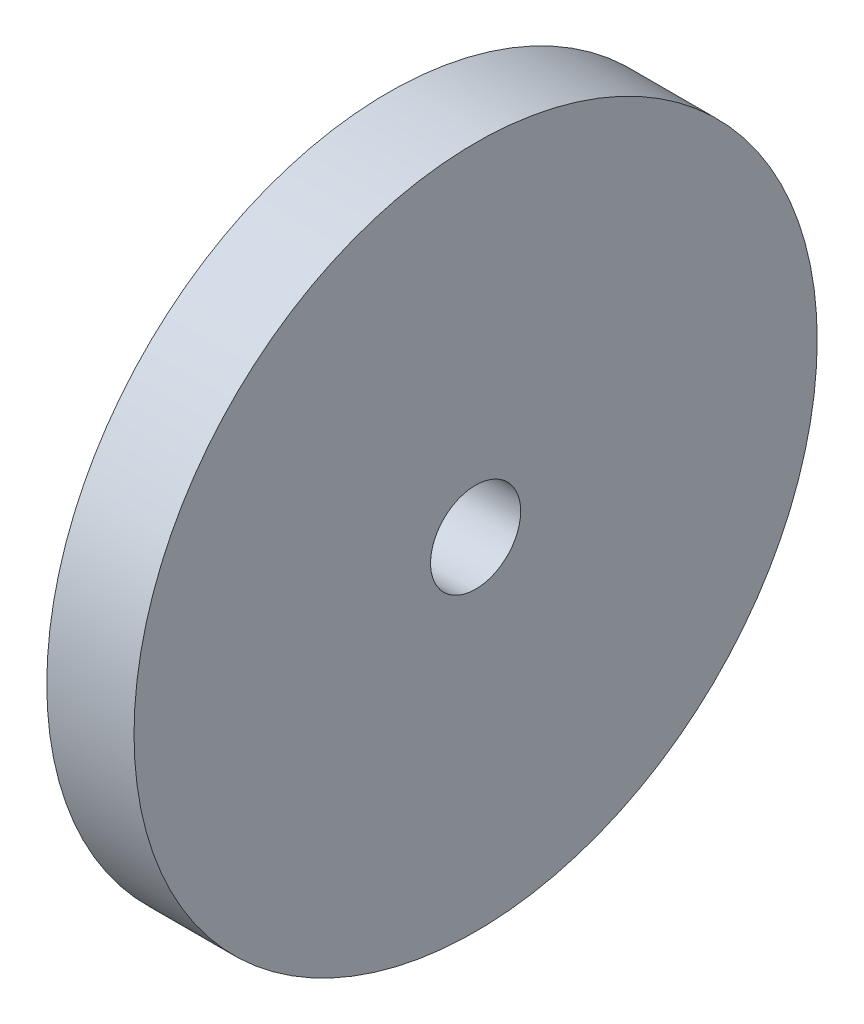
SolidWorks part; units mm, degrees
ref_plane "Front Plane" through (0, 0, 0) normal (0, 0, 1) x (1, 0, 0)
ref_plane "Top Plane" through (0, 0, 0) normal (0, 1, 0) x (1, 0, 0)
ref_plane "Right Plane" through (0, 0, 0) normal (1, 0, 0) x (0, 0, -1)
sketch "Sketch1" plane through (0, 0, 0) normal (1, 0, 0) x (0, 0, -1)
  circle A0 centre (0, 0) radius 11.75
  circle A1 centre (0, 0) radius 1.55
  dimension "D1" = 23.5
  dimension "D2" = 3.1
extrude "Boss-Extrude1" add sketch "Sketch1" along normal blind 3
